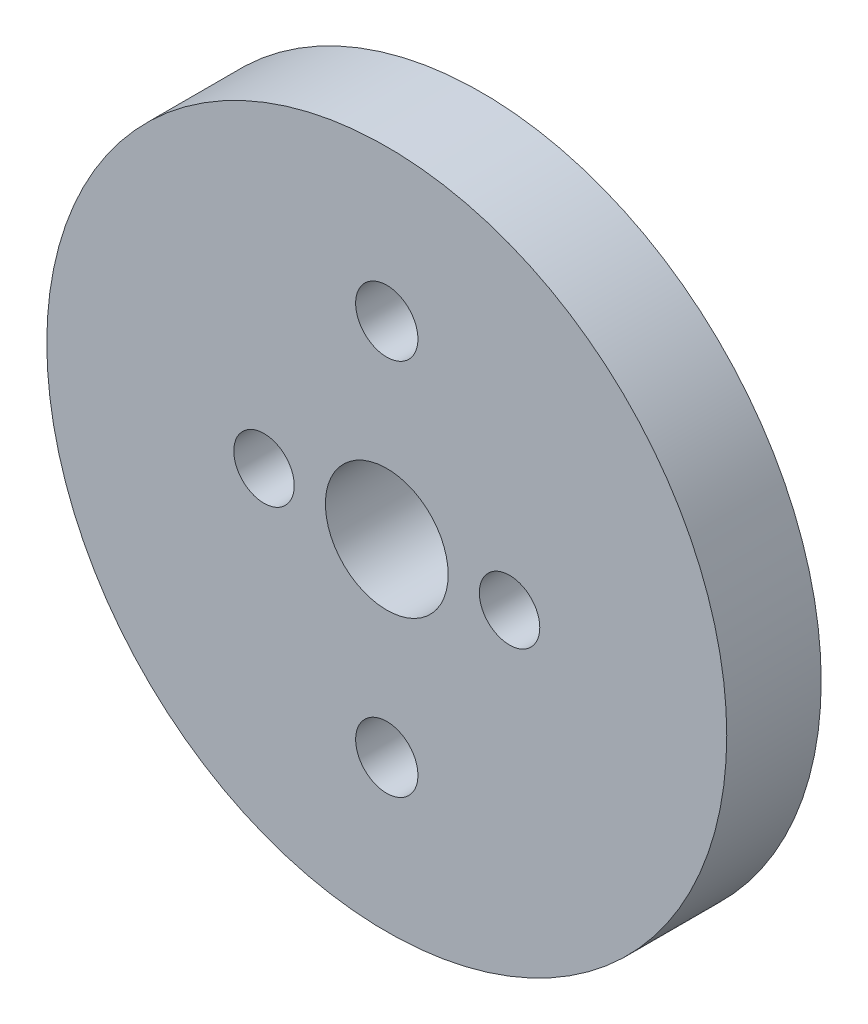
SolidWorks part; units mm, degrees
material "5052-H34"
ref_plane "正面" through (0, 0, 0) normal (0, 0, 1) x (1, 0, 0)
ref_plane "平面" through (0, 0, 0) normal (0, 1, 0) x (1, 0, 0)
ref_plane "右側面" through (0, 0, 0) normal (1, 0, 0) x (0, 0, -1)
sketch "ｽｹｯﾁ1" plane through (0, 0, 0) normal (0, 0, 1) x (1, 0, 0)
  line L0 (0, 0) -> (6.5, 0) construction
  line L1 (0, 0) -> (0, 18) construction
  circle A0 centre (0, 0) radius 18
  circle A1 centre (0, 0) radius 3.25
  circle A2 centre (6.5, 0) radius 1.6
  circle A3 centre (-6.5, 0) radius 1.6
  dimension "D1" = 36
  dimension "D2" = 6.5
  dimension "D3" = 3.2
  dimension "D4" = 13
extrude "ﾎﾞｽ - 押し出し1" add sketch "ｽｹｯﾁ1" along normal blind 5
sketch "ｽｹｯﾁ2" plane through (0, 0, 5) normal (0, 0, 1) x (1, 0, 0)
  line L0 (18, 0) -> (0, 0) construction
  line L1 (0, 0) -> (0, 10) construction
  circle A0 centre (0, 0) radius 18 construction
  circle A1 centre (0, 10) radius 1.65
  circle A2 centre (0, -10) radius 1.65
  dimension "D1" = 3.3
  dimension "D2" = 20
extrude "ｶｯﾄ - 押し出し1" cut sketch "ｽｹｯﾁ2" against normal through all
